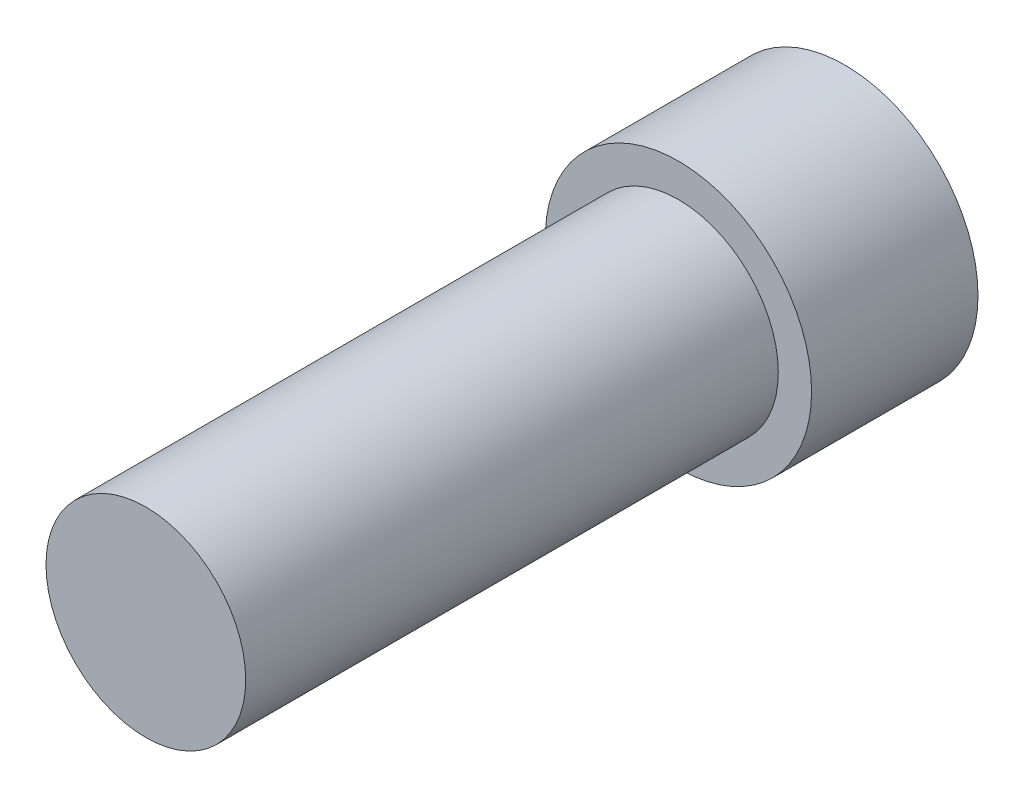
SolidWorks part; units mm, degrees
ref_plane "前视基准面" through (0, 0, 0) normal (0, 0, 1) x (1, 0, 0)
ref_plane "上视基准面" through (0, 0, 0) normal (0, 1, 0) x (1, 0, 0)
ref_plane "右视基准面" through (0, 0, 0) normal (1, 0, 0) x (0, 0, -1)
sketch "草图1" plane through (0, 0, 0) normal (0, 0, 1) x (1, 0, 0)
  line L1 (-0.9563, 1.0811) -> (-1.4144, -0.2877)
  line L2 (-1.4144, -0.2877) -> (-0.4581, -1.3688)
  line L3 (-0.4581, -1.3688) -> (0.9563, -1.0811)
  line L4 (0.9563, -1.0811) -> (1.4144, 0.2877)
  line L5 (1.4144, 0.2877) -> (0.4581, 1.3688)
  line L6 (0.4581, 1.3688) -> (-0.9563, 1.0811)
  circle A0 centre (0, 0) radius 2
  circle A1 centre (0, 0) radius 1.25 construction
  point P3 (1.1854, -0.3967)
  dimension "D1" = 4
  dimension "D2" = 2.5
extrude "凸台-拉伸1" add sketch "草图1" along normal blind 2.5
ref_plane "基准面1" through (0, 0, 2.5) normal (0, 0, 1) x (1, 0, 0)
sketch "草图2" plane through (0, 0, 2.5) normal (0, 0, 1) x (1, 0, 0)
  circle A0 centre (0, 0) radius 1.5
  dimension "D1" = 3
extrude "凸台-拉伸2" add sketch "草图2" along normal blind 8
